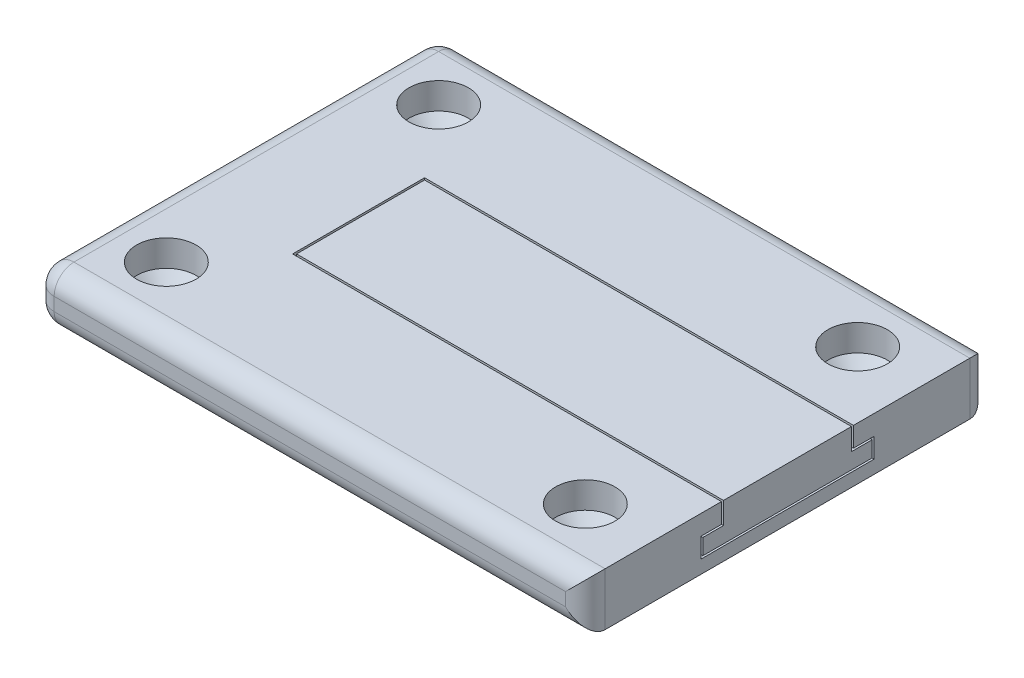
SolidWorks part; units mm, degrees
ref_plane "Front Plane" through (0, 0, 0) normal (0, 0, 1) x (1, 0, 0)
ref_plane "Top Plane" through (0, 0, 0) normal (0, 1, 0) x (1, 0, 0)
ref_plane "Right Plane" through (0, 0, 0) normal (1, 0, 0) x (0, 0, -1)
sketch "Sketch1" plane through (0, 0, 0) normal (0, 1, 0) x (1, 0, 0)
  line L1 (-31.75, 20.6375) -> (31.75, 20.6375) construction
  line L2 (-31.75, 20.6375) -> (-31.75, -20.6375) construction
  line L3 (-31.75, -20.6375) -> (31.75, -20.6375) construction
  line L4 (31.75, 20.6375) -> (31.75, -20.6375) construction
  line L5 (-31.75, 20.6375) -> (31.75, -20.6375) construction
  line L6 (-31.75, -20.6375) -> (31.75, 20.6375) construction
  line L7 (-41.75, 30.6375) -> (41.75, 30.6375)
  line L8 (-41.75, 30.6375) -> (-41.75, -30.6375)
  line L9 (-41.75, -30.6375) -> (41.75, -30.6375)
  line L10 (41.75, 30.6375) -> (41.75, -30.6375)
  line L11 (-41.75, 30.6375) -> (41.75, -30.6375) construction
  line L12 (-41.75, -30.6375) -> (41.75, 30.6375) construction
  circle A0 centre (-31.75, 20.6375) radius 2.5
  circle A1 centre (-31.75, -20.6375) radius 2.5
  circle A2 centre (31.75, -20.6375) radius 2.5
  circle A3 centre (31.75, 20.6375) radius 2.5
  point P0 (0, 0)
  point P10 (0, 0)
  dimension "D3" = 5
  dimension "D1" = 63.5
  dimension "D2" = 41.275
  dimension "D4" = 10
  dimension "D5" = 10
extrude "Boss-Extrude1" add sketch "Sketch1" along normal blind 4
chamfer "Chamfer1" distance 2 angle 45 4 edges at (-31.75, 4, 23.1375) (31.75, 4, -18.1375) (31.75, 4, 23.1375) (-31.75, 4, -18.1375)
sketch "Sketch3" plane through (0, 4, 0) normal (0, 1, 0) x (1, 0, 0)
  line L4 (41.75, -30.6375) -> (41.75, 30.6375)
  line L5 (41.75, 30.6375) -> (-41.75, 30.6375)
  line L6 (-41.75, 30.6375) -> (-41.75, -30.6375)
  line L7 (-41.75, -30.6375) -> (41.75, -30.6375)
  line L8 (41.75, -30.6375) -> (41.75, 30.6375)
  line L9 (41.75, 30.6375) -> (-41.75, 30.6375)
  line L10 (-41.75, 30.6375) -> (-41.75, -30.6375)
  line L11 (-41.75, -30.6375) -> (41.75, -30.6375)
  circle A0 centre (31.75, 20.6375) radius 4.5 construction
  circle A1 centre (31.75, -20.6375) radius 4.5 construction
  circle A2 centre (-31.75, -20.6375) radius 4.5 construction
  circle A3 centre (-31.75, 20.6375) radius 4.5 construction
  circle A4 centre (31.75, 20.6375) radius 4.5
  circle A5 centre (31.75, -20.6375) radius 4.5
  circle A6 centre (-31.75, -20.6375) radius 4.5
  circle A7 centre (-31.75, 20.6375) radius 4.5
  dimension "D1" = 0
extrude "Boss-Extrude2" add sketch "Sketch3" along normal blind 4
sketch "Sketch4" plane through (41.75, 0, 0) normal (1, 0, 0) x (0, 0, -1)
  line L0 (-16.1375, 8) -> (-16.1375, 0) construction
  line L1 (-16.1375, 8) -> (-25.1375, 8) construction
  line L2 (30.6375, 8) -> (-30.6375, 8) construction
  line L3 (30.6375, 0) -> (-30.6375, 0) construction
  line L4 (16.1375, 8) -> (16.1375, 0) construction
  line L5 (25.1375, 8) -> (16.1375, 8) construction
  line L6 (16.1375, 8) -> (16.1375, 4) construction
  line L7 (-16.1375, 4) -> (-16.1375, 8) construction
  line L8 (0, 8) -> (0, 0) construction
  line L9 (-30.6375, 8) -> (30.6375, 8) construction
  line L24 (-13.1375, 5) -> (13.1375, 5)
  line L25 (-13.1375, 5) -> (-13.1375, 2)
  line L26 (-13.1375, 2) -> (13.1375, 2)
  line L27 (13.1375, 5) -> (13.1375, 2)
  line L28 (-10, 8) -> (10, 8)
  line L29 (-10, 8) -> (-10, 5)
  line L30 (-10, 5) -> (10, 5)
  line L31 (10, 8) -> (10, 5)
  point P26 (0, 2)
  point P31 (0, 8)
  line M5 (30.6375, 8) -> (-30.6375, 8)
  dimension "D1" = 3
  dimension "D2" = 3
  dimension "D3" = 3
  dimension "D4" = 20
extrude "Cut-Extrude1" cut sketch "Sketch4" against normal blind 65 contours L27 L24 L25 L26 | L31 L29 L24 M5
sketch "Sketch5" plane through (41.75, 0, 0) normal (1, 0, 0) x (0, 0, -1)
  line L8 (-9.7, 8) -> (9.7, 8)
  line L9 (10, 8) -> (-10, 8) construction
  line L16 (12.8375, 2.3) -> (12.8375, 4.7)
  line L17 (12.8375, 4.7) -> (9.7, 4.7)
  line L18 (9.7, 4.7) -> (9.7, 7.7)
  line L19 (9.7, 7.7) -> (-9.7, 7.7)
  line L20 (-9.7, 7.7) -> (-9.7, 4.7)
  line L21 (-9.7, 4.7) -> (-12.8375, 4.7)
  line L22 (-12.8375, 4.7) -> (-12.8375, 2.3)
  line L23 (-12.8375, 2.3) -> (12.8375, 2.3)
  line L24 (12.8375, 2.3) -> (12.8375, 4.7)
  line L25 (12.8375, 4.7) -> (9.7, 4.7)
  line L26 (9.7, 4.7) -> (9.7, 8)
  line L28 (-9.7, 8) -> (-9.7, 4.7)
  line L29 (-9.7, 4.7) -> (-12.8375, 4.7)
  line L30 (-12.8375, 4.7) -> (-12.8375, 2.3)
  line L31 (-12.8375, 2.3) -> (12.8375, 2.3)
  dimension "D1" = 0.3
extrude "Boss-Extrude3" add sketch "Sketch5" against normal offset from surface (64.7 mm away) 0.3 separate body up to face at (-23.25, 5, 0)
fillet "Fillet1" radius 3 10 edges at (41.75, 4, -30.6375) (0, 8, -30.6375) (0, 0, -30.6375) (-41.75, 4, -30.6375) (-41.75, 8, 0) (-41.75, 0, 0) (-41.75, 4, 30.6375) (0, 8, 30.6375) (41.75, 4, 30.6375) (0, 0, 30.6375)
equation "\"mount hole\"= 5"
equation "\"0.365.00mm\"=65"
